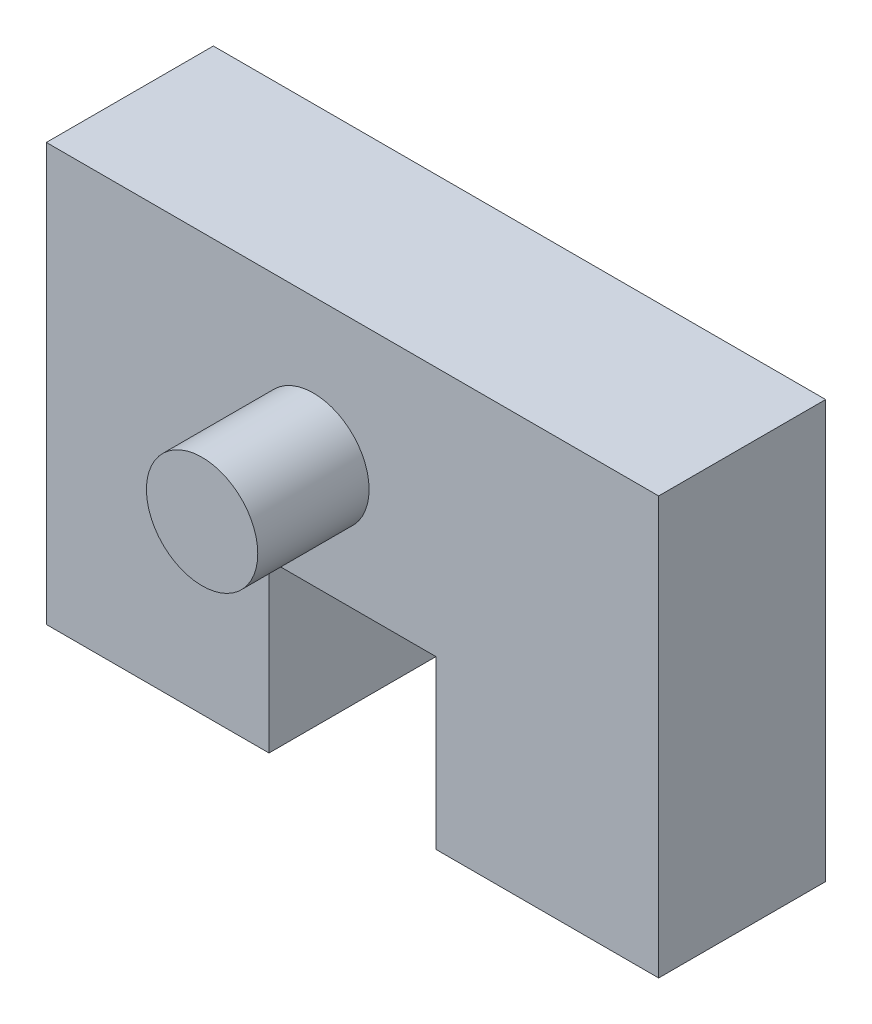
SolidWorks part; units mm, degrees
ref_plane "Plan de face" through (0, 0, 0) normal (0, 0, 1) x (1, 0, 0)
ref_plane "Plan de dessus" through (0, 0, 0) normal (0, 1, 0) x (1, 0, 0)
ref_plane "Plan de droite" through (0, 0, 0) normal (1, 0, 0) x (0, 0, -1)
sketch "Esquisse1" plane through (0, 0, 0) normal (0, 0, 1) x (1, 0, 0)
  line L1 (0, 0) -> (-22, 0)
  line L2 (0, 0) -> (0, 15)
  line L3 (0, 15) -> (-22, 15)
  line L4 (-22, 0) -> (-22, 15)
  line L5 (-22, 0) -> (-14, 0)
  line L6 (-22, 0) -> (-22, 6)
  line L7 (-22, 6) -> (-14, 6)
  line L8 (-14, 0) -> (-14, 6)
  line L9 (-8, 0) -> (0, 0)
  line L10 (-8, 0) -> (-8, 6)
  line L11 (-8, 6) -> (0, 6)
  line L12 (0, 0) -> (0, 6)
  line L13 (-8, 6) -> (-14, 6)
  line L14 (-8, 6) -> (-8, 0)
  line L15 (-8, 0) -> (-14, 0)
  line L16 (-14, 6) -> (-14, 0)
  dimension "D1" = 22
  dimension "D2" = 15
  dimension "D3" = 8
  dimension "D4" = 6
extrude "Boss.-Extru.1" add sketch "Esquisse1" along normal blind 6 contours L13 L11 L2 L3 L4 L7 | L11 L10 L1 L2 | L1 L8 L7 L4
sketch "Esquisse2" plane through (0, 0, 6) normal (0, 0, 1) x (1, 0, 0)
  circle A0 centre (-12.4038, 10) radius 2
  dimension "D1" = 4
extrude "Boss.-Extru.2" add sketch "Esquisse2" along normal blind 4
